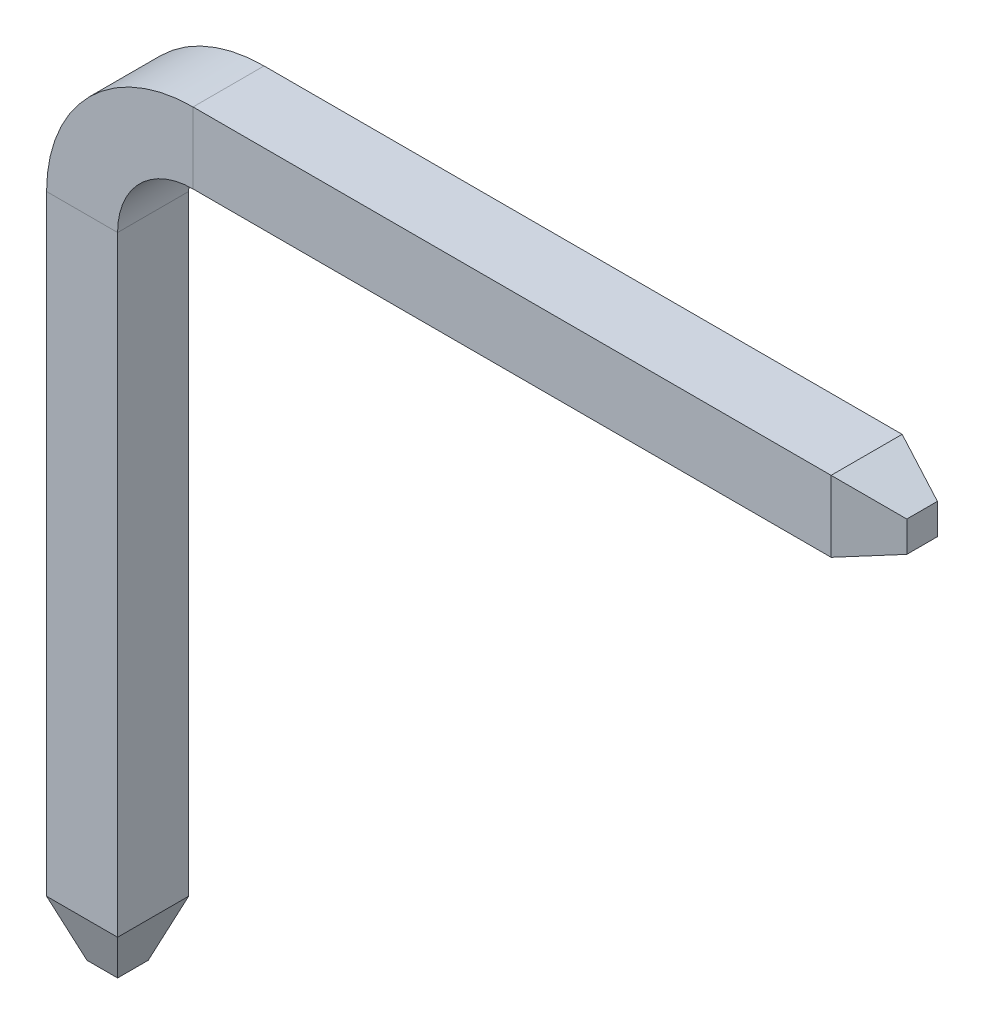
SolidWorks part; units mm, degrees
ref_plane "Спереди" through (0, 0, 0) normal (0, 0, 1) x (1, 0, 0)
ref_plane "Сверху" through (0, 0, 0) normal (0, 1, 0) x (1, 0, 0)
ref_plane "Справа" through (0, 0, 0) normal (1, 0, 0) x (0, 0, -1)
sketch "Эскиз3" plane through (0, 0, 0) normal (0, 1, 0) x (1, 0, 0)
  line L1 (-1.25, 1.25) -> (1.25, 1.25) construction
  line L2 (-1.25, 1.25) -> (-1.25, -1.25) construction
  line L3 (-1.25, -1.25) -> (1.25, -1.25) construction
  line L4 (1.25, 1.25) -> (1.25, -1.25) construction
  line L5 (-1.25, 1.25) -> (1.25, -1.25) construction
  line L6 (-1.25, -1.25) -> (1.25, 1.25) construction
  point P0 (0, 0)
  dimension "D1" = 2.5
sketch "Эскиз4" plane through (0, 0, 0) normal (0, 0, 1) x (1, 0, 0)
  line L0 (-1.25, 1.25) -> (1.25, 1.25) construction
  line L1 (-1.25, 1.25) -> (-1.25, -1.25) construction
  line L2 (-1.25, -1.25) -> (1.25, -1.25) construction
  line L3 (1.25, 1.25) -> (1.25, -1.25) construction
  line L4 (-1.25, 1.25) -> (1.25, -1.25) construction
  line L5 (-1.25, -1.25) -> (1.25, 1.25) construction
  point P0 (0, 0)
  dimension "D1" = 2.5
sketch "Эскиз1" plane through (0, 0, 0) normal (0, 1, 0) x (1, 0, 0)
  line L1 (-0.32, 0.32) -> (0.32, 0.32)
  line L2 (-0.32, 0.32) -> (-0.32, -0.32)
  line L3 (-0.32, -0.32) -> (0.32, -0.32)
  line L4 (0.32, 0.32) -> (0.32, -0.32)
  line L5 (-0.32, 0.32) -> (0.32, -0.32) construction
  line L6 (-0.32, -0.32) -> (0.32, 0.32) construction
  point P0 (0, 0)
  dimension "D1" = 0.64
sketch "Эскиз2" plane through (0, 0, 0) normal (0, 0, 1) x (1, 0, 0)
  line L0 (0, 0) -> (0, 1.75)
  line L1 (1, 2.75) -> (7.25, 2.75)
  line L3 (0, 0) -> (0, -4.25)
  line L4 (1.25, 1.25) -> (1.25, -1.25) construction
  line L6 (-1.25, -1.25) -> (1.25, -1.25) construction
  arc A0 (0, 1.75) -> (1, 2.75) centre (1, 1.75) cw
  dimension "D4" = 1
  dimension "D1" = 6
  dimension "D2" = 1.5
  dimension "D3" = 3
sweep "По траектории1" add profiles "Эскиз1" path "Эскиз2"
chamfer "Фаска1" distance 0.5 angle 20 4 edges at (7.25, 2.75, 0.32) (7.25, 3.07, 0) (7.25, 2.75, -0.32) (7.25, 2.43, 0)
chamfer "Фаска2" distance 0.5 angle 20 4 edges at (0, -4.25, -0.32) (-0.32, -4.25, 0) (0, -4.25, 0.32) (0.32, -4.25, 0)
sketch "Эскиз5" plane through (0, 0, 0) normal (0, 0, 1) x (1, 0, 0)
  line L0 (0, -8.1573) -> (0, 6.6577) construction
  line L2 (-2.4103, 2.75) -> (5.9307, 2.75) construction
  line L3 (7.25, 2.888) -> (7.25, 2.612) construction
  point P7 (7.25, 2.75)
